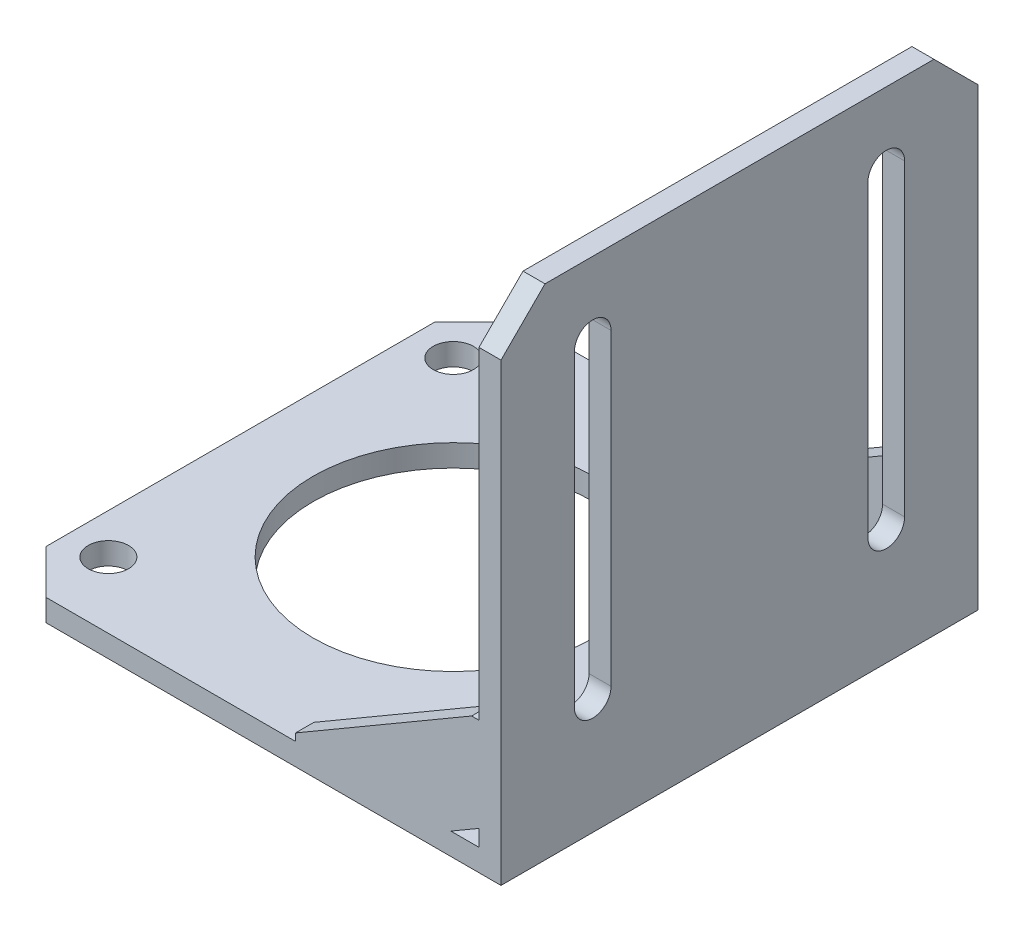
SolidWorks part; units mm, degrees
ref_plane "Płaszczyzna przednia" through (0, 0, 0) normal (0, 0, 1) x (1, 0, 0)
ref_plane "Płaszczyzna górna" through (0, 0, 0) normal (0, 1, 0) x (1, 0, 0)
ref_plane "Płaszczyzna prawa" through (0, 0, 0) normal (1, 0, 0) x (0, 0, -1)
sketch "Sketch1" plane through (0, 0, 0) normal (0, 1, 0) x (1, 0, 0)
  line L1 (34, -32.5) -> (-34, -32.5)
  line L2 (34, -32.5) -> (34, 32.5)
  line L3 (34, 32.5) -> (-34, 32.5)
  line L4 (-34, -32.5) -> (-34, 32.5)
  line L5 (34, -32.5) -> (-34, 32.5) construction
  line L6 (34, 32.5) -> (-34, -32.5) construction
  point P0 (0, 0)
  dimension "D1" = 68
  dimension "D2" = 65
extrude "Boss-Extrude1" add sketch "Sketch1" along normal blind 3
sketch "Sketch2" plane through (0, 0, 32.5) normal (0, 0, 1) x (1, 0, 0)
  line L1 (34, 0) -> (31, 0)
  line L2 (34, 0) -> (34, 68)
  line L3 (34, 68) -> (31, 68)
  line L4 (31, 0) -> (31, 68)
  dimension "D1" = 3
  dimension "D2" = 68
extrude "Boss-Extrude2" add sketch "Sketch2" against normal blind 65
chamfer "Chamfer1" distance 6 angle 45 4 edges at (32.5, 68, 32.5) (32.5, 68, -32.5) (-34, 1.5, -32.5) (-34, 1.5, 32.5)
sketch "Sketch4" plane through (0, 3, 0) normal (0, 1, 0) x (1, 0, 0)
  line L0 (-5, 27.9535) -> (-5, -22.0219) construction
  line L1 (-28.8856, 0) -> (25.2607, 0) construction
  line L2 (-34, 26.5) -> (-34, -26.5) construction
  line L3 (-28, -32.5) -> (31, -32.5) construction
  line L4 (31, 32.5) -> (-28, 32.5) construction
  circle A0 centre (-28.5, 23.5) radius 2.75
  circle A1 centre (-28.5, -23.5) radius 2.75
  circle A2 centre (18.6, -23.5) radius 2.75
  circle A3 centre (18.5, 23.5) radius 2.75
  circle A4 centre (-5, 0) radius 19.1
  dimension "D1" = 47
  dimension "D6" = 29
  dimension "D7" = 38.2
  dimension "D2" = 47.1
  dimension "D3" = 47
  dimension "D4" = 47
extrude "Cut-Extrude2" cut sketch "Sketch4" against normal blind 65
sketch "Sketch5" plane through (31, 0, 0) normal (-1, 0, 0) x (0, 0, 1)
  line L0 (-20, 58) -> (-20, 16) construction
  line L1 (-17.5, 58) -> (-17.5, 16)
  line L2 (-22.5, 58) -> (-22.5, 16)
  line L3 (20, 58) -> (20, 16) construction
  line L4 (22.5, 58) -> (22.5, 16)
  line L5 (17.5, 58) -> (17.5, 16)
  line L6 (-26.5, 68) -> (26.5, 68) construction
  line L7 (-32.5, 62) -> (-32.5, 3) construction
  arc A0 (-17.5, 58) -> (-22.5, 58) centre (-20, 58) ccw
  arc A1 (-22.5, 16) -> (-17.5, 16) centre (-20, 16) ccw
  arc A2 (22.5, 58) -> (17.5, 58) centre (20, 58) ccw
  arc A3 (17.5, 16) -> (22.5, 16) centre (20, 16) ccw
  point P2 (-20, 37)
  point P7 (20, 37)
  point P18 (0, 0)
  dimension "D1" = 10
  dimension "D2" = 10
  dimension "D3" = 40
  dimension "D4" = 5
  dimension "D5" = 5
  dimension "D6" = 42
  dimension "D7" = 42
  dimension "D8" = 12.5
extrude "Cut-Extrude3" cut sketch "Sketch5" against normal blind 65
sketch "Sketch6" plane through (0, 0, 32.5) normal (0, 0, 1) x (1, 0, 0)
  line L0 (6, 3) -> (6, 4)
  line L1 (-28, 3) -> (31, 3) construction
  line L4 (31, 62) -> (31, 3) construction
  line L6 (27.1714, 3) -> (6, 3)
  line L7 (6, 4) -> (30, 18)
  line L8 (30, 18) -> (31, 18)
  line L9 (31, 18) -> (31, 5.2334)
  line L10 (31, 5.2334) -> (27.1714, 3)
  dimension "D1" = 25
  dimension "D2" = 15
  dimension "D3" = 1
  dimension "D4" = 1
  dimension "D5" = 0
extrude "Boss-Extrude3" add sketch "Sketch6" against normal blind 2.5
sketch "Sketch7" plane through (0, 0, -32.5) normal (0, 0, -1) x (-1, 0, 0)
  line L0 (-31, 18) -> (-30, 18)
  line L1 (-30, 18) -> (-6, 4)
  line L2 (-6, 4) -> (-6, 3)
  line L3 (-6, 3) -> (-27.1714, 3)
  line L4 (-27.1714, 3) -> (-31, 5.2334)
  line L5 (-31, 5.2334) -> (-31, 18)
extrude "Boss-Extrude4" add sketch "Sketch7" against normal blind 2.5
